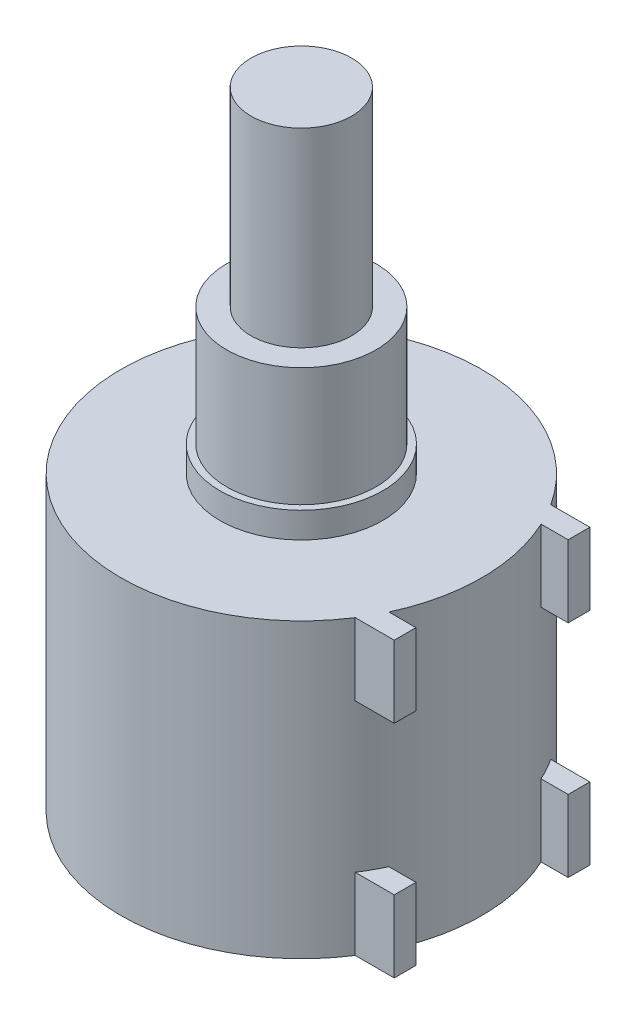
SolidWorks part; units mm, degrees
ref_plane "Front" through (0, 0, 0) normal (0, 0, 1) x (1, 0, 0)
ref_plane "Top" through (0, 0, 0) normal (0, 1, 0) x (1, 0, 0)
ref_plane "Right" through (0, 0, 0) normal (1, 0, 0) x (0, 0, -1)
sketch "Sketch1" plane through (0, 0, 0) normal (0, 0, 1) x (1, 0, 0)
  line L0 (-11.2014, 18.161) -> (-11.2014, 0)
  line L1 (-11.2014, 0) -> (0, 0)
  line L2 (-11.2014, 18.161) -> (-5.0546, 18.161)
  line L3 (-4.6355, 19.7612) -> (-4.6355, 27.1272)
  line L4 (-4.6355, 27.1272) -> (-3.1242, 27.1272)
  line L5 (-3.1242, 27.1272) -> (-3.1242, 38.9382)
  line L6 (-3.1242, 38.9382) -> (0, 38.9382)
  line L7 (0, 38.9382) -> (0, 0)
  line L8 (0, 0) -> (0, -23.6016) construction
  line L9 (-4.6355, 19.7612) -> (-5.0546, 19.7612)
  line L10 (-5.0546, 19.7612) -> (-5.0546, 18.161)
  dimension "D1" = 22.4028
  dimension "D2" = 9.271
  dimension "D3" = 6.2484
  dimension "D4" = 38.9382
  dimension "D5" = 27.1272
  dimension "D6" = 18.161
  dimension "D7" = 19.7612
  dimension "D8" = 10.1092
revolve "Revolve1" add sketch "Sketch1" angle 360 about L8
ref_plane "Plane1" through (11.8364, 0, 0) normal (1, 0, 0) x (0, 0, -1)
sketch "Sketch2" plane through (11.8364, 0, 0) normal (1, 0, 0) x (0, 0, -1)
  line L0 (0, 0) -> (0, -2.8161) construction
  line L1 (-6.0706, 18.161) -> (-4.7244, 18.161)
  line L2 (-6.0706, 18.161) -> (-6.0706, 13.6906)
  line L3 (-6.0706, 13.6906) -> (-4.7244, 13.6906)
  line L4 (-4.7244, 18.161) -> (-4.7244, 13.6906)
  line L5 (-6.0706, 18.161) -> (-4.7244, 13.6906) construction
  line L6 (-6.0706, 13.6906) -> (-4.7244, 18.161) construction
  line L7 (11.2014, 18.161) -> (-11.2014, 18.161) construction
  line L8 (0, 0) -> (0, 18.161) construction
  line L9 (0, 9.0805) -> (-15.1369, 9.0805) construction
  line L10 (-6.0706, 4.4704) -> (-4.7244, 0) construction
  line L11 (-6.0706, 0) -> (-4.7244, 4.4704) construction
  line L12 (-4.7244, 0) -> (-4.7244, 4.4704)
  line L13 (-6.0706, 4.4704) -> (-4.7244, 4.4704)
  line L14 (-6.0706, 0) -> (-6.0706, 4.4704)
  line L15 (-6.0706, 0) -> (-4.7244, 0)
  point P0 (-5.3975, 15.9258)
  point P17 (-5.3975, 2.2352)
  dimension "D1" = 4.4704
  dimension "D2" = 1.3462
  dimension "D3" = 12.1412
extrude "Boss-Extrude1" add sketch "Sketch2" against normal up to surface (1.6801 mm away)
mirror "Mirror1" about plane through (0, 0, 0) normal (0, 0, 1) of "Boss-Extrude1"
